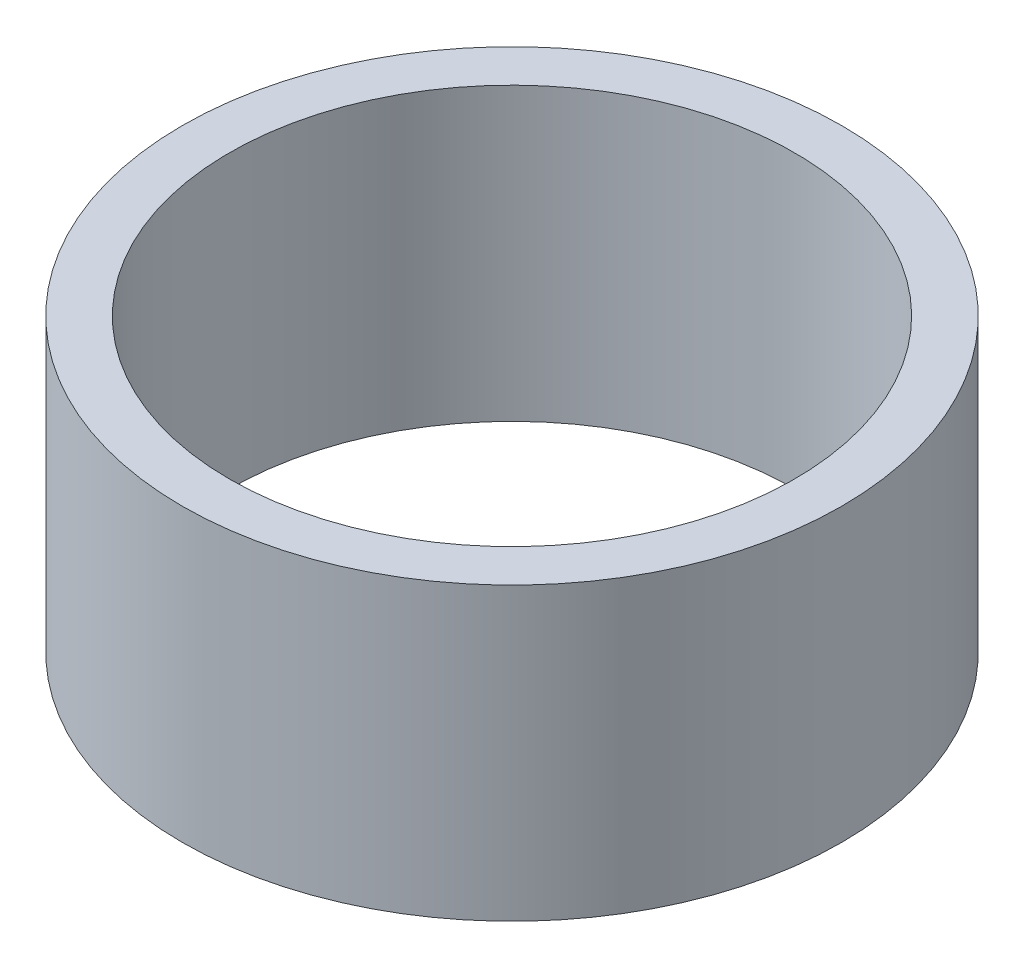
SolidWorks part; units mm, degrees
ref_plane "Plano frontal" through (0, 0, 0) normal (0, 0, 1) x (1, 0, 0)
ref_plane "Plano superior" through (0, 0, 0) normal (0, 1, 0) x (1, 0, 0)
ref_plane "Plano direito" through (0, 0, 0) normal (1, 0, 0) x (0, 0, -1)
sketch "Esboço1" plane through (0, 0, 0) normal (0, 1, 0) x (1, 0, 0)
  circle A0 centre (0, 0) radius 33
  circle A1 centre (0, 0) radius 38.5
  dimension "D1" = 66
  dimension "D2" = 77
extrude "Ressalto-extrusão1" add sketch "Esboço1" along normal blind 34
